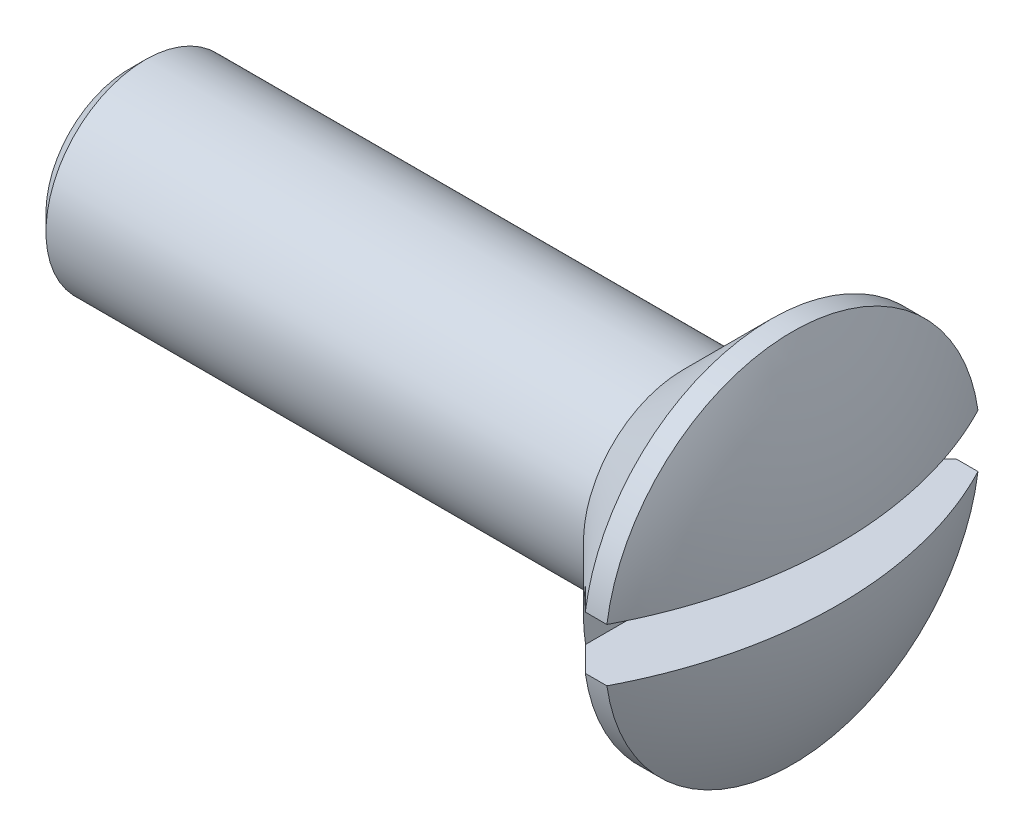
SolidWorks part; units mm, degrees
material "AISI 1020"
ref_plane "Front Plane" through (0, 0, 0) normal (0, 0, 1) x (1, 0, 0)
ref_plane "Top Plane" through (0, 0, 0) normal (0, 1, 0) x (1, 0, 0)
ref_plane "Right Plane" through (0, 0, 0) normal (1, 0, 0) x (0, 0, -1)
sketch "Sketch1" plane through (0, 0, 0) normal (0, 0, 1) x (1, 0, 0)
  line L0 (0, 0) -> (-21.4, 0) construction
  line L1 (-1.4, 5.65) -> (-2.05, 5.65)
  line L2 (-2.05, 5.65) -> (-4.7, 3)
  line L3 (-4.7, 3) -> (-21.4, 3)
  line L4 (-21.4, 3) -> (-21.4, 0)
  line L5 (-21.4, 0) -> (0, 0)
  arc A0 (0, 0) -> (-1.4, 5.65) centre (-12.1009, 0) ccw
  dimension "Diam" = 6
  dimension "G_diam" = 11.3
  dimension "G_sf_plotis" = 1.4
  dimension "G_plotis" = 3.3
  dimension "D5" = 45
  dimension "Ilgis" = 20
revolve "Revolve1" add sketch "Sketch1" angle 360 about L0
cosmetic thread "Cosmetic Thread1" parameters "Sr_ilgis"=16.7, "Sr_diam"=5
sketch "Sketch2" plane through (0, 0, 0) normal (1, 0, 0) x (0, 0, -1)
  line L0 (-5.65, -0.8) -> (5.65, 0.8) construction
  line L1 (-5.65, 0.8) -> (5.65, 0.8)
  line L2 (-5.65, 0.8) -> (-5.65, -0.8)
  line L3 (-5.65, -0.8) -> (5.65, -0.8)
  line L4 (5.65, 0.8) -> (5.65, -0.8)
  circle A1 centre (0, 0) radius 5.65 construction
  dimension "Y_plotis" = 1.6
extrude "Cut-Extrude1" cut sketch "Sketch2" against normal blind 2.8
chamfer "Chamfer1" distance 0.5 angle 45 1 edges at (-21.4, 3, 0)
